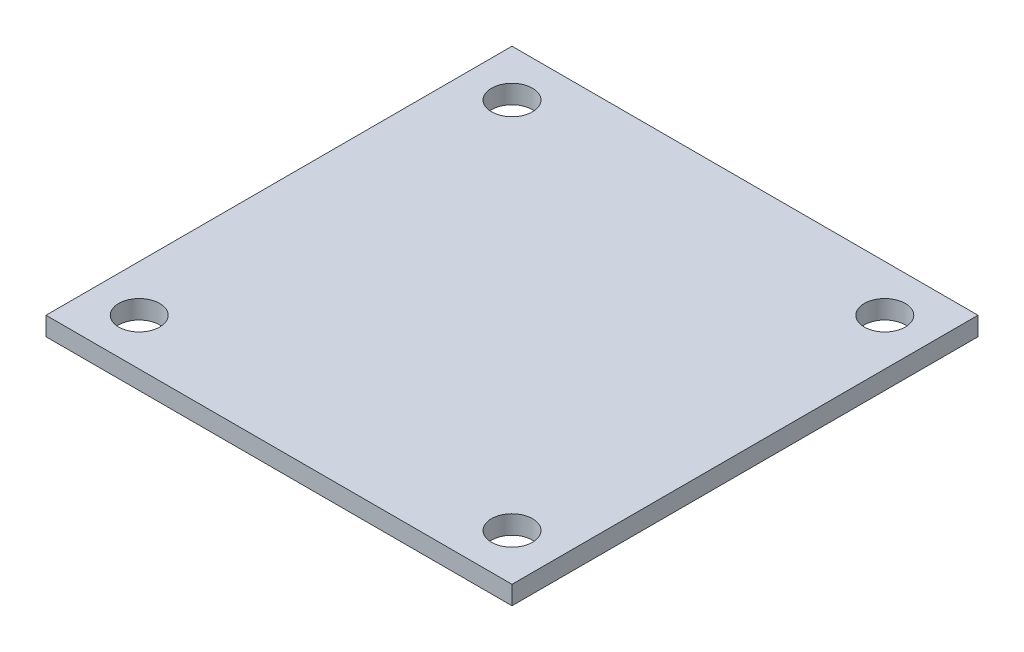
SolidWorks part; units mm, degrees
ref_plane "Front Plane" through (0, 0, 0) normal (0, 0, 1) x (1, 0, 0)
ref_plane "Top Plane" through (0, 0, 0) normal (0, 1, 0) x (1, 0, 0)
ref_plane "Right Plane" through (0, 0, 0) normal (1, 0, 0) x (0, 0, -1)
sketch "Sketch1" plane through (0, 0, 0) normal (0, 1, 0) x (1, 0, 0)
  line L1 (-3175, -3175) -> (3175, -3175)
  line L2 (-3175, -3175) -> (-3175, 3175)
  line L3 (-3175, 3175) -> (3175, 3175)
  line L4 (3175, -3175) -> (3175, 3175)
  line L5 (-3175, -3175) -> (3175, 3175) construction
  line L6 (-3175, 3175) -> (3175, -3175) construction
  line L7 (-2540, -2540) -> (2540, -2540)
  line L8 (-2540, -2540) -> (-2540, 2540)
  line L9 (-2540, 2540) -> (2540, 2540) construction
  line L10 (2540, -2540) -> (2540, 2540)
  line L11 (-2540, -2540) -> (2540, 2540) construction
  line L12 (-2540, 2540) -> (2540, -2540) construction
  circle A0 centre (0, 0) radius 1447.8 construction
  circle A1 centre (-2540, -2540) radius 279.4
  circle A2 centre (-2540, 2540) radius 279.4
  circle A3 centre (2540, 2540) radius 279.4
  circle A4 centre (2540, -2540) radius 279.4
  point P0 (0, 0)
  dimension "D3" = 2895.6
  dimension "D4" = 5080
  dimension "D6" = 558.8
  dimension "D1" = 6350
  dimension "D2" = 6350
  dimension "D5" = 5080
extrude "Boss-Extrude1" add sketch "Sketch1" along normal blind 254
